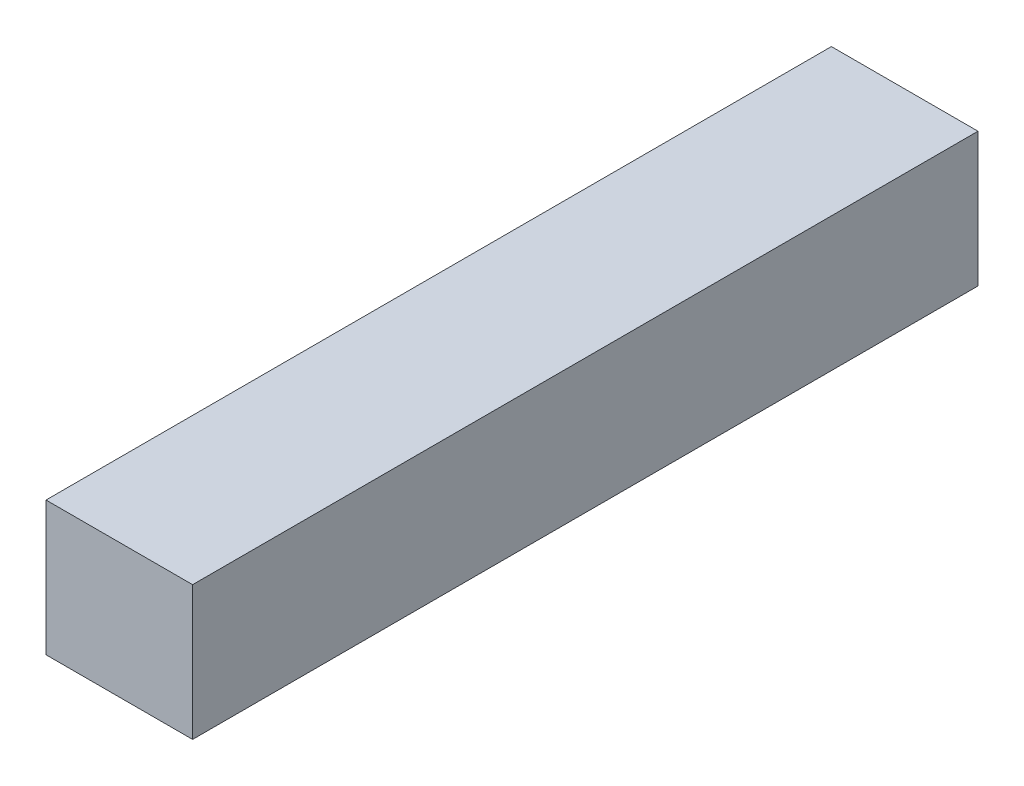
SolidWorks part; units mm, degrees
ref_plane "Plano frontal" through (0, 0, 0) normal (0, 0, 1) x (1, 0, 0)
ref_plane "Plano superior" through (0, 0, 0) normal (0, 1, 0) x (1, 0, 0)
ref_plane "Plano direito" through (0, 0, 0) normal (1, 0, 0) x (0, 0, -1)
sketch "Esboço1" plane through (0, 0, 0) normal (0, 0, 1) x (1, 0, 0)
  line L0 (0, 0) -> (14, 0)
  line L1 (14, 0) -> (14, 12.8)
  line L2 (14, 12.8) -> (0, 12.8)
  line L3 (0, 12.8) -> (0, 0)
  dimension "D1" = 14
  dimension "D2" = 12.8
extrude "Ressalto-extrusão1" add sketch "Esboço1" along normal blind 75
